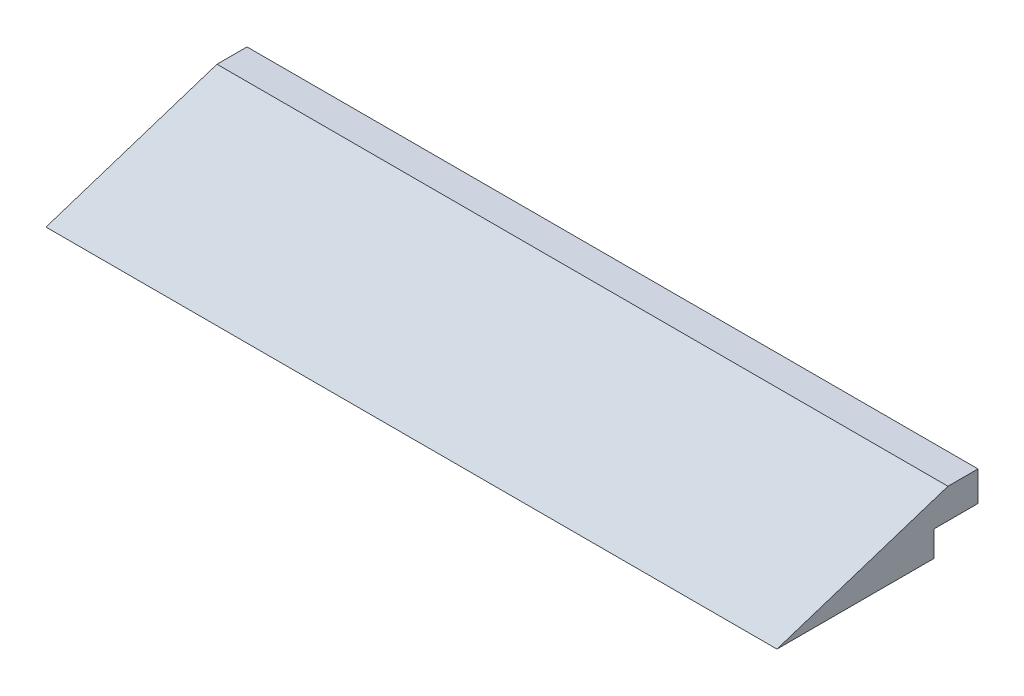
SolidWorks part; units mm, degrees
material "Aleación 1060"
ref_plane "Alzado" through (0, 0, 0) normal (0, 0, 1) x (1, 0, 0)
ref_plane "Planta" through (0, 0, 0) normal (0, 1, 0) x (1, 0, 0)
ref_plane "Vista lateral" through (0, 0, 0) normal (1, 0, 0) x (0, 0, -1)
sketch "Croquis1" plane through (0, 0, 0) normal (0, 1, 0) x (1, 0, 0)
  line L1 (-100, 27.5) -> (100, 27.5)
  line L2 (-100, 27.5) -> (-100, -27.5)
  line L3 (-100, -27.5) -> (100, -27.5)
  line L4 (100, 27.5) -> (100, -27.5)
  line L5 (-100, 27.5) -> (100, -27.5) construction
  line L6 (-100, -27.5) -> (100, 27.5) construction
  point P0 (0, 0)
  dimension "D1" = 200
  dimension "D2" = 55
extrude "Saliente-Extruir1" add sketch "Croquis1" along normal blind 15.2
sketch "Croquis2" plane through (100, 0, 0) normal (1, 0, 0) x (0, 0, -1)
  line L0 (-27.5, 0) -> (1.0317, 9.2705)
  line L3 (-27.5, 0) -> (27.5, 0) construction
  line L4 (27.5, 7) -> (15.5, 7)
  line L5 (27.5, 15.2) -> (27.5, 0) construction
  line L6 (15.5, 7) -> (15.5, 0)
  line L9 (-27.5, 15.2) -> (-27.5, 0)
  line L10 (15.5, 0) -> (27.5, 0)
  line L11 (27.5, 0) -> (27.5, 7)
  line L12 (1.0317, 9.2705) -> (19.2808, 15.2)
  line L13 (-27.5, 15.2) -> (27.5, 15.2) construction
  line L14 (19.2808, 15.2) -> (-27.5, 15.2)
  dimension "D1" = 18
  dimension "D2" = 7
  dimension "D3" = 12
  dimension "D4" = 30
extrude "Cortar-Extruir1" cut sketch "Croquis2" against normal through all and the other way through all
